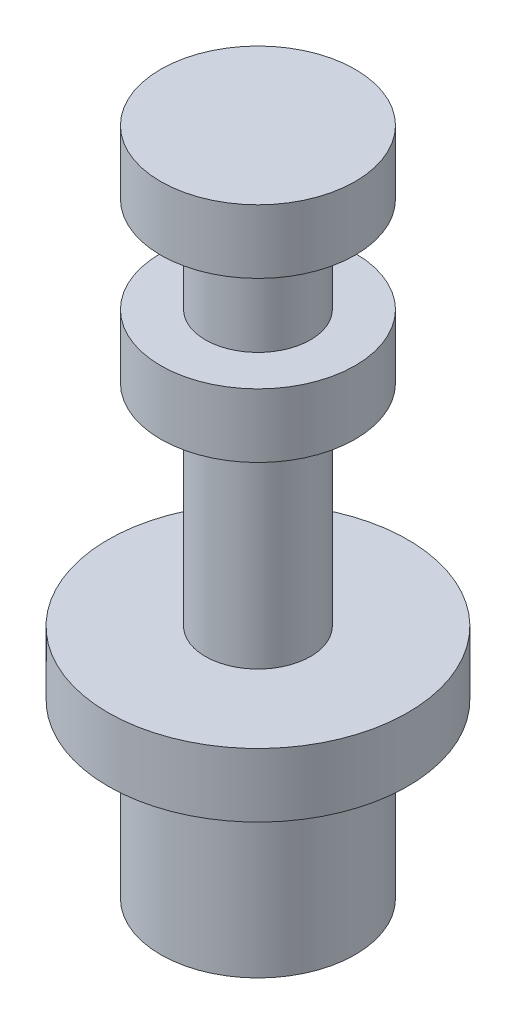
SolidWorks part; units mm, degrees
ref_plane "Alzado" through (0, 0, 0) normal (0, 0, 1) x (1, 0, 0)
ref_plane "Planta" through (0, 0, 0) normal (0, 1, 0) x (1, 0, 0)
ref_plane "Vista lateral" through (0, 0, 0) normal (1, 0, 0) x (0, 0, -1)
sketch "Croquis2" plane through (0, 0, 0) normal (0, 1, 0) x (1, 0, 0)
  circle A0 centre (0, 0) radius 0.7747
  dimension "D1" = 1.5494
extrude "Saliente-Extruir1" add sketch "Croquis2" along normal blind 1.3716
sketch "Croquis3" plane through (0, 1.3716, 0) normal (0, 1, 0) x (1, 0, 0)
  circle A0 centre (0, 0) radius 1.1938
  dimension "D1" = 2.3876
extrude "Saliente-Extruir2" add sketch "Croquis3" along normal blind 0.508
sketch "Croquis4" plane through (0, 1.8796, 0) normal (0, 1, 0) x (1, 0, 0)
  circle A0 centre (0, 0) radius 0.4191
  dimension "D1" = 0.8382
extrude "Saliente-Extruir3" add sketch "Croquis4" along normal blind 1.6764
sketch "Croquis5" plane through (0, 3.556, 0) normal (0, 1, 0) x (1, 0, 0)
  circle A0 centre (0, 0) radius 0.7747
  dimension "D1" = 1.5494
extrude "Saliente-Extruir4" add sketch "Croquis5" along normal blind 0.508
sketch "Croquis6" plane through (0, 4.064, 0) normal (0, 1, 0) x (1, 0, 0)
  circle A0 centre (0, 0) radius 0.4191
  dimension "D1" = 0.8382
extrude "Saliente-Extruir5" add sketch "Croquis6" along normal blind 0.762
sketch "Croquis7" plane through (0, 4.826, 0) normal (0, 1, 0) x (1, 0, 0)
  circle A0 centre (0, 0) radius 0.7747
  dimension "D1" = 1.5494
extrude "Saliente-Extruir6" add sketch "Croquis7" along normal blind 0.508
